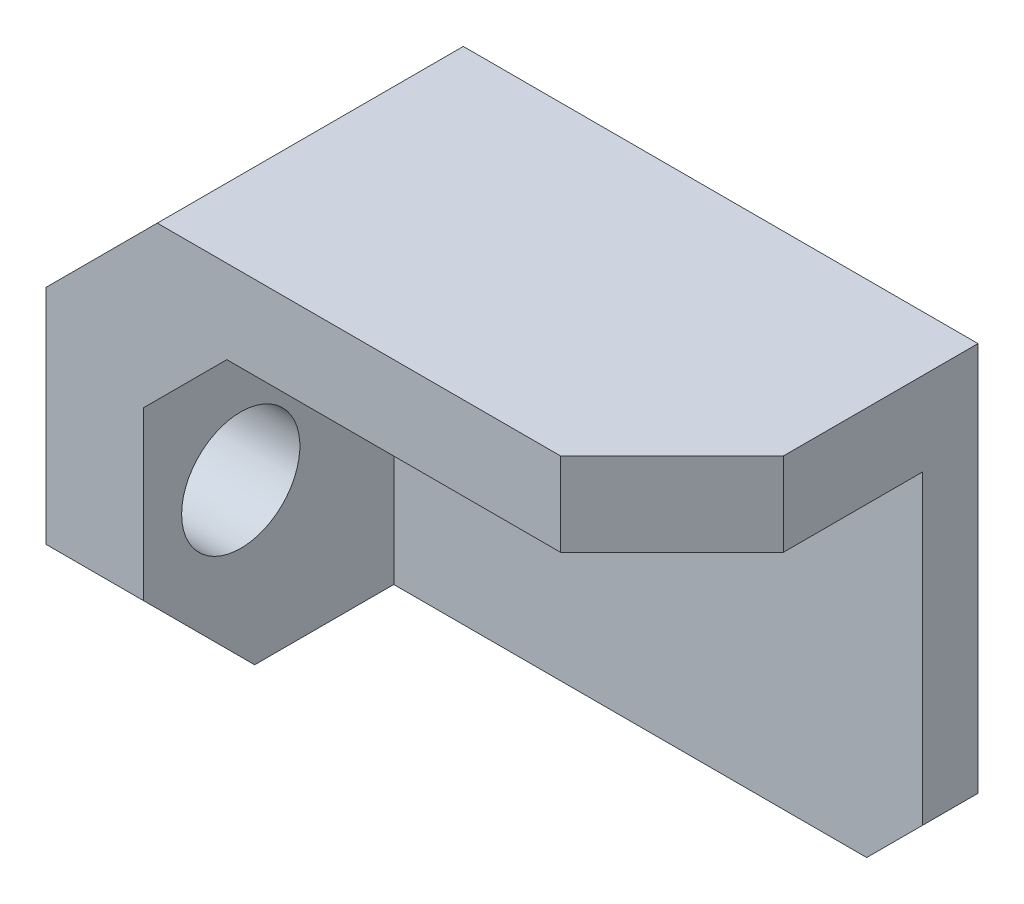
SolidWorks part; units mm, degrees
ref_plane "Plan de face" through (0, 0, 0) normal (0, 0, 1) x (1, 0, 0)
ref_plane "Plan de dessus" through (0, 0, 0) normal (0, 1, 0) x (1, 0, 0)
ref_plane "Plan de droite" through (0, 0, 0) normal (1, 0, 0) x (0, 0, -1)
sketch "Esquisse1" plane through (0, 0, 0) normal (0, 0, 1) x (1, 0, 0)
  line L1 (0, 0) -> (45, 0)
  line L2 (0, 0) -> (0, 32)
  line L3 (0, 32) -> (45, 32)
  line L4 (45, 0) -> (45, 32)
  dimension "D1" = 32
  dimension "D2" = 45
extrude "Boss.-Extru.1" add sketch "Esquisse1" along normal blind 22
sketch "Esquisse2" plane through (0, 0, 22) normal (0, 0, 1) x (1, 0, 0)
  line L0 (45, 16) -> (22.5, 16) construction
  line L1 (45, 0) -> (45, 32) construction
  circle A0 centre (22.5, 16) radius 5.25
  dimension "D1" = 10.5
  dimension "D2" = 22.5
extrude "Enlèv. mat.-Extru.1" cut sketch "Esquisse2" against normal through all
sketch "Esquisse3" plane through (0, 0, 0) normal (-1, 0, 0) x (0, 0, 1)
  line L0 (15, 0) -> (15, 12) construction
  line L2 (0, 32) -> (0, 0) construction
  line L3 (22, 0) -> (0, 0) construction
  circle A0 centre (15, 12) radius 4.25
  point P5 (0, 0)
  point P6 (15, 0)
  dimension "D1" = 8.5
  dimension "D3" = 15
  dimension "D2" = 12
extrude "Enlèv. mat.-Extru.2" cut sketch "Esquisse3" against normal through all both and the other way through all
sketch "Esquisse4" plane through (45, 0, 0) normal (1, 0, 0) x (0, 0, -1)
  line L0 (-22, 0) -> (-22, 32) construction
  line L1 (-22, 0) -> (-4, 0)
  line L2 (-22, 0) -> (-22, 26)
  line L3 (-22, 26) -> (-4, 26)
  line L4 (-4, 0) -> (-4, 26)
  line L5 (0, 0) -> (0, 32) construction
  line L7 (-22, 32) -> (0, 32) construction
  line L8 (-22, 0) -> (0, 0) construction
  point P8 (-4, 0)
  dimension "D1" = 4
  dimension "D3" = 6
extrude "Enlèv. mat.-Extru.3" cut sketch "Esquisse4" against normal blind 38
sketch "Esquisse5" plane through (7, 0, 0) normal (1, 0, 0) x (0, 0, -1)
  circle A0 centre (-15, 12) radius 6.5
  dimension "D1" = 13
chamfer "Chanfrein1" distance 8 angle 45 3 edges at (45, 29, 22) (3.5, 0, 22) (0, 32, 11)
sketch "Esquisse6" plane through (0, 0, 4) normal (0, 0, 1) x (1, 0, 0)
  circle A0 centre (22.5, 16) radius 8
  dimension "D1" = 16
sketch "Esquisse7" plane through (0, 0, 22) normal (0, 0, 1) x (1, 0, 0)
  line L0 (7, 26) -> (13, 26)
  line L1 (7, 26) -> (45, 26) construction
  line L2 (13, 26) -> (7, 20)
  line L3 (7, 0) -> (7, 26) construction
  line L4 (7, 20) -> (7, 26)
  dimension "D1" = 6
  dimension "D2" = 6
extrude "Boss.-Extru.2" add sketch "Esquisse7" against normal up to vertex (18 mm away) up to point (7, 26, 4)
chamfer "Chanfrein2" distance 4 angle 45 1 edges at (45, 0, 2)
